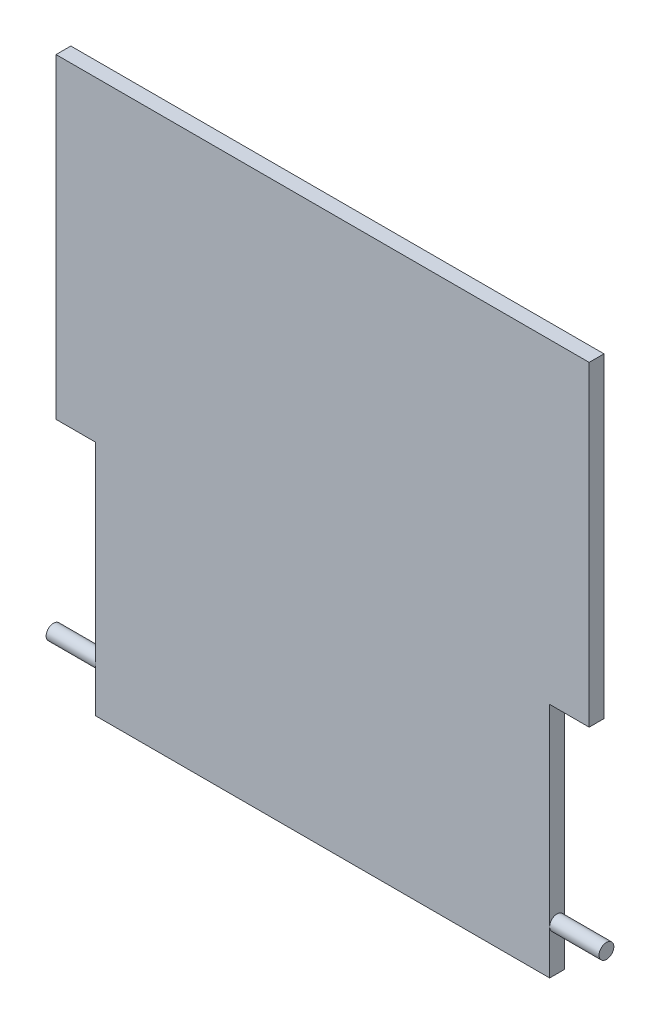
SolidWorks part; units mm, degrees
ref_plane "Front Plane" through (0, 0, 0) normal (0, 0, 1) x (1, 0, 0)
ref_plane "Top Plane" through (0, 0, 0) normal (0, 1, 0) x (1, 0, 0)
ref_plane "Right Plane" through (0, 0, 0) normal (1, 0, 0) x (0, 0, -1)
sketch "Sketch1" plane through (0, 0, 0) normal (0, 0, 1) x (1, 0, 0)
  line L0 (-18.2563, 0) -> (18.2563, 0)
  line L1 (18.2563, 0) -> (18.2563, 19.05)
  line L2 (18.2563, 19.05) -> (21.4312, 19.05)
  line L3 (21.4312, 19.05) -> (21.4312, 44.45)
  line L4 (21.4312, 44.45) -> (-21.4312, 44.45)
  line L5 (-21.4312, 44.45) -> (-21.4312, 19.05)
  line L6 (-21.4312, 19.05) -> (-18.2563, 19.05)
  line L7 (-18.2563, 19.05) -> (-18.2563, 0)
  point P3 (0, 0)
  point P10 (-21.4313, 40.4666)
  point P11 (-21.4312, 34.8586)
  point P12 (-21.4312, 9.0754)
  point P13 (-21.4312, 37.7158)
  point P14 (0, 0)
  dimension "D1" = 42.8625
  dimension "D2" = 44.45
  dimension "D3" = 3.175
  dimension "D4" = 19.05
extrude "Boss-Extrude1" add sketch "Sketch1" along normal mid plane 1.1906 contours L7 L0 L1 L2 L3 L4 L5 L6
sketch "Sketch2" plane through (0, 0, 0) normal (1, 0, 0) x (0, 0, -1)
  line L0 (-0.5953, 0) -> (0.5953, 0) construction
  circle A0 centre (0, 3.5719) radius 0.5953
  point P2 (0, 0)
  point P3 (0, 0)
  dimension "D1" = 1.1906
  dimension "D2" = 3.5719
extrude "Boss-Extrude2" add sketch "Sketch2" along normal mid plane 44.45 contours A0
